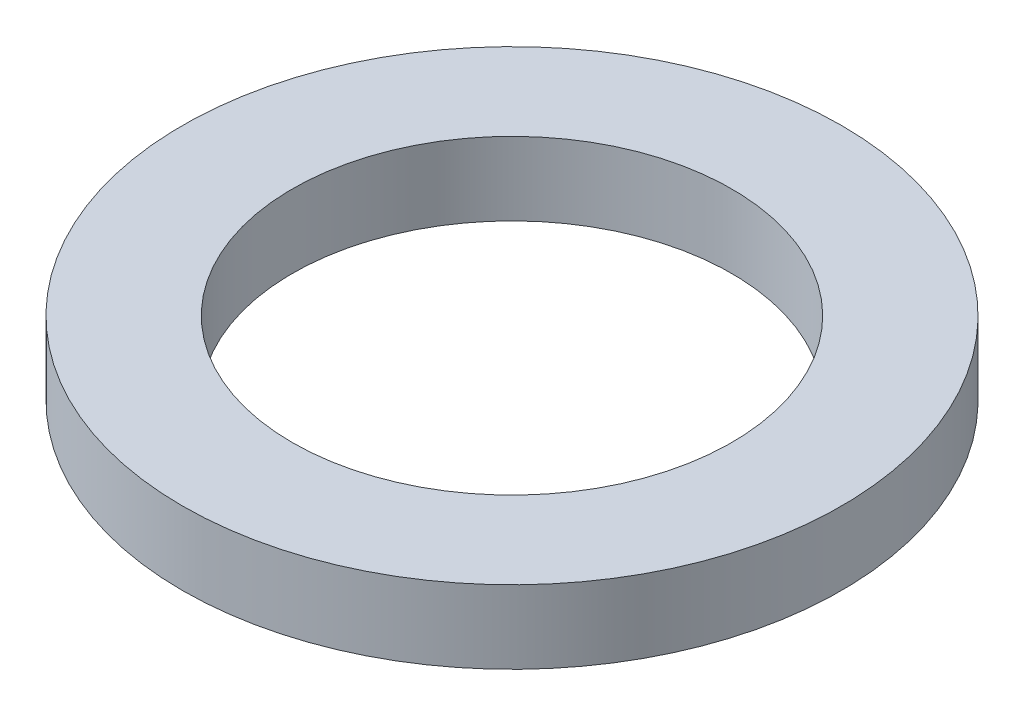
SolidWorks part; units mm, degrees
ref_plane "前视基准面" through (0, 0, 0) normal (0, 0, 1) x (1, 0, 0)
ref_plane "上视基准面" through (0, 0, 0) normal (0, 1, 0) x (1, 0, 0)
ref_plane "右视基准面" through (0, 0, 0) normal (1, 0, 0) x (0, 0, -1)
other "Configuration Table"
sketch "草图1" plane through (0, 0, 0) normal (0, 1, 0) x (1, 0, 0)
  circle A0 centre (0, 0) radius 2.25
  circle A1 centre (0, 0) radius 1.5
  dimension "D1" = 4.5
  dimension "D2" = 3
extrude "凸台-拉伸1" add sketch "草图1" along normal blind 0.5
